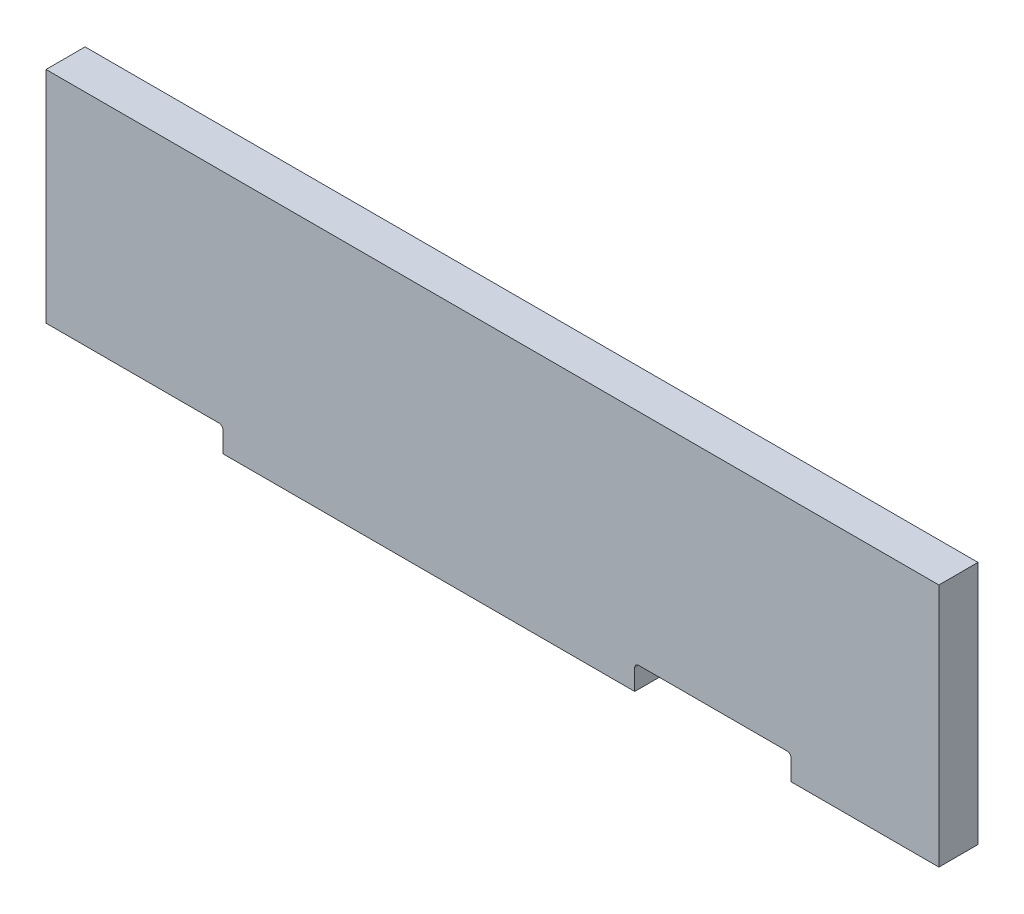
SolidWorks part; units mm, degrees
ref_plane "Front Plane" through (0, 0, 0) normal (0, 0, 1) x (1, 0, 0)
ref_plane "Top Plane" through (0, 0, 0) normal (0, 1, 0) x (1, 0, 0)
ref_plane "Right Plane" through (0, 0, 0) normal (1, 0, 0) x (0, 0, -1)
sketch "Sketch1" plane through (0, 0, 0) normal (0, 0, 1) x (1, 0, 0)
  line L1 (300, 0) -> (-135, 0)
  line L2 (300, 0) -> (300, 119.05)
  line L3 (300, 119.05) -> (-135, 119.05)
  line L4 (-135, 0) -> (-135, 119.05)
  line L5 (-135, 119.05) -> (300, 119.05) construction
  dimension "D1" = 119.05
  dimension "D2" = 435
extrude "Boss-Extrude1" add sketch "Sketch1" along normal blind 19.05
sketch "Sketch2" plane through (0, 0, 19.05) normal (0, 0, 1) x (1, 0, 0)
  line L1 (-48.8, 12) -> (-125, 12) construction
  line L2 (-48.8, 0) -> (-48.8, 12) construction
  line L3 (-135, 0) -> (300, 0) construction
  line L4 (151.8, 0) -> (151.8, 12) construction
  line L5 (151.8, 12) -> (228, 12) construction
  line L6 (228, 12) -> (228, 0) construction
  line L8 (-48.8, 12) -> (-125, 12)
  line L9 (-48.8, 0) -> (-48.8, 12)
  line L10 (-125, 0) -> (-48.8, 0)
  line L11 (151.8, 0) -> (151.8, 12)
  line L12 (151.8, 12) -> (228, 12)
  line L13 (228, 12) -> (228, 0)
  line L14 (151.8, 0) -> (228, 0)
  line L15 (-125, 12) -> (-135, 12)
  line L16 (-135, 119.05) -> (-135, 0) construction
  line L17 (-135, 12) -> (-135, 0)
  line L18 (-135, 0) -> (-125, 0)
extrude "Cut-Extrude1" cut sketch "Sketch2" against normal through all
fillet "Fillet1" radius 2 3 edges at (151.8, 12, 9.525) (228, 12, 9.525) (-48.8, 12, 9.525)
